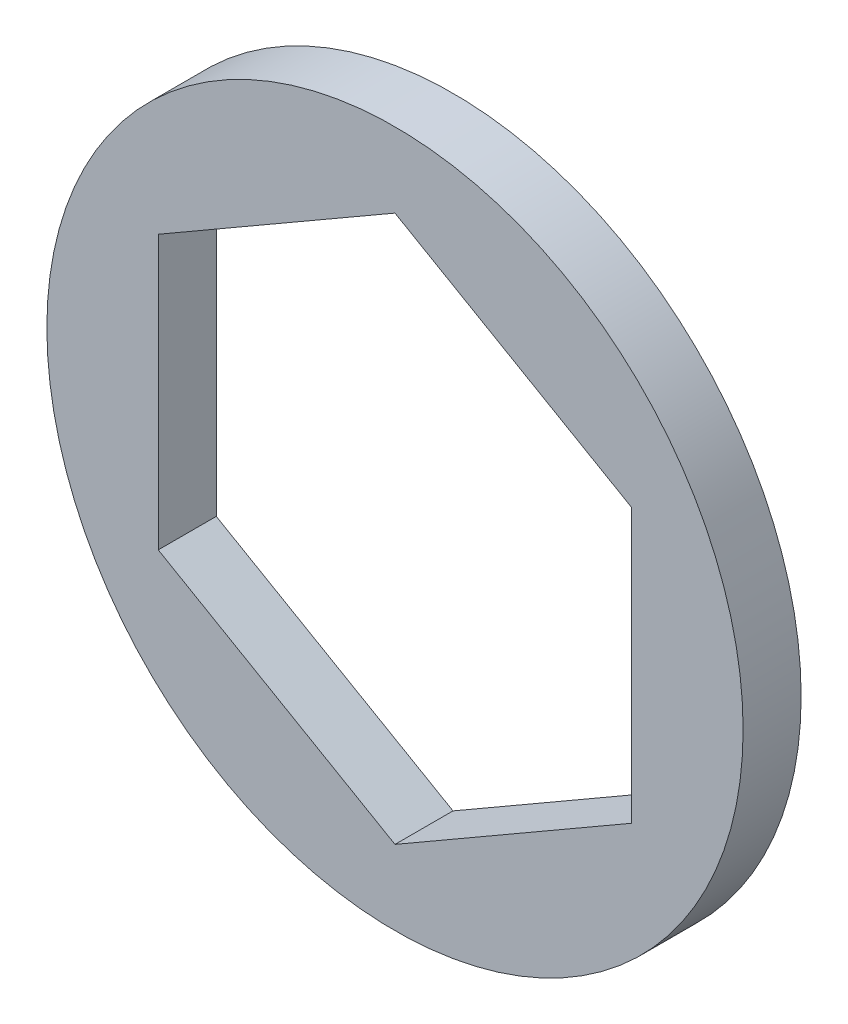
SolidWorks part; units mm, degrees
material "PET"
ref_plane "Front Plane" through (0, 0, 0) normal (0, 0, 1) x (1, 0, 0)
ref_plane "Top Plane" through (0, 0, 0) normal (0, 1, 0) x (1, 0, 0)
ref_plane "Right Plane" through (0, 0, 0) normal (1, 0, 0) x (0, 0, -1)
sketch "Sketch1" plane through (0, 0, 0) normal (0, 0, 1) x (1, 0, 0)
  line L1 (0, 7.479) -> (-6.477, 3.7395)
  line L2 (-6.477, 3.7395) -> (-6.477, -3.7395)
  line L3 (-6.477, -3.7395) -> (0, -7.479)
  line L4 (0, -7.479) -> (6.477, -3.7395)
  line L5 (6.477, -3.7395) -> (6.477, 3.7395)
  line L6 (6.477, 3.7395) -> (0, 7.479)
  circle A0 centre (0, 0) radius 6.477 construction
  circle A1 centre (0, 0) radius 9.525
  dimension "D1" = 12.954
  dimension "D2" = 19.05
extrude "Boss-Extrude1" add sketch "Sketch1" along normal mid plane 1.5875
